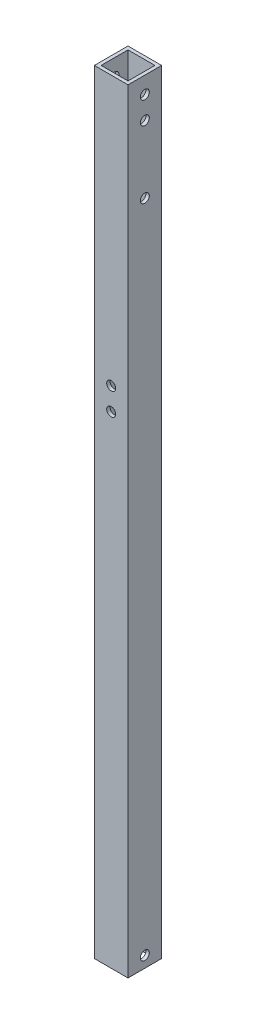
SolidWorks part; units mm, degrees
material "5052-H34"
ref_plane "正面" through (0, 0, 0) normal (0, 0, 1) x (1, 0, 0)
ref_plane "平面" through (0, 0, 0) normal (0, 1, 0) x (1, 0, 0)
ref_plane "右側面" through (0, 0, 0) normal (1, 0, 0) x (0, 0, -1)
sketch "ｽｹｯﾁ1" plane through (0, 0, 0) normal (0, 1, 0) x (1, 0, 0)
  line L1 (-7.5, 7.5) -> (7.5, 7.5)
  line L2 (-7.5, 7.5) -> (-7.5, -7.5)
  line L3 (-7.5, -7.5) -> (7.5, -7.5)
  line L4 (7.5, 7.5) -> (7.5, -7.5)
  line L5 (-7.5, 7.5) -> (7.5, -7.5) construction
  line L6 (-7.5, -7.5) -> (7.5, 7.5) construction
  point P0 (0, 0)
  dimension "D1" = 15
  dimension "D2" = 15
extrude "押し出し-薄板1" add sketch "ｽｹｯﾁ1" along normal blind 345 thin
sketch "ｽｹｯﾁ2" plane through (7.5, 0, 0) normal (1, 0, 0) x (0, 0, -1)
  line L0 (0, 0) -> (0, 5) construction
  line L1 (0, 345) -> (0, 297.5) construction
  line L2 (-7.5, 345) -> (7.5, 345) construction
  circle A0 centre (0, 5) radius 2
  circle A1 centre (0, 297.5) radius 2
  circle A2 centre (0, 337.5) radius 2
  circle A3 centre (0, 327.5) radius 2
  dimension "D1" = 4
  dimension "D3" = 4
  dimension "D6" = 30
  dimension "D2" = 5
  dimension "D4" = 7.5
  dimension "D5" = 40
extrude "ｶｯﾄ - 押し出し1" cut sketch "ｽｹｯﾁ2" against normal through all
sketch "ｽｹｯﾁ3" plane through (0, 0, 7.5) normal (0, 0, 1) x (1, 0, 0)
  line L0 (0, 0) -> (0, 225) construction
  line L1 (-7.5, 0) -> (7.5, 0) construction
  circle A0 centre (0, 225) radius 2
  circle A3 centre (0, 215) radius 2
  dimension "D2" = 4
  dimension "D3" = 10
  dimension "D1" = 225
extrude "ｶｯﾄ - 押し出し2" cut sketch "ｽｹｯﾁ3" against normal through all
